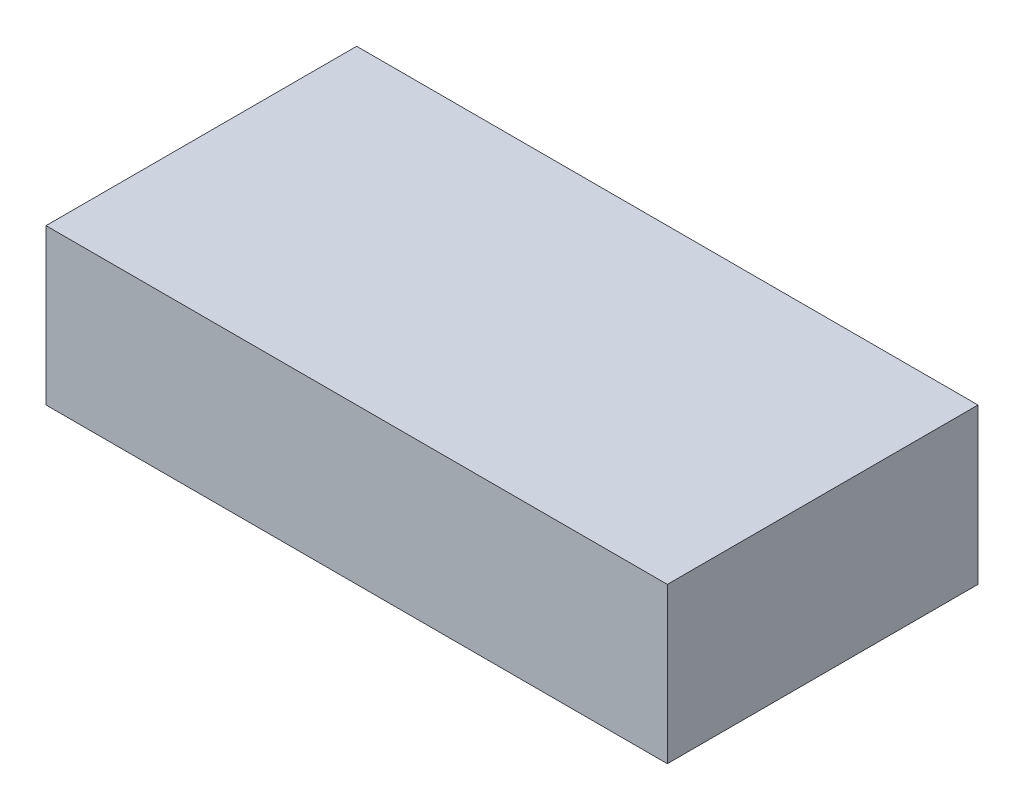
SolidWorks part; units mm, degrees
material "1060 Alloy"
ref_plane "Front Plane" through (0, 0, 0) normal (0, 0, 1) x (1, 0, 0)
ref_plane "Top Plane" through (0, 0, 0) normal (0, 1, 0) x (1, 0, 0)
ref_plane "Right Plane" through (0, 0, 0) normal (1, 0, 0) x (0, 0, -1)
sketch "Sketch1" plane through (0, 0, 0) normal (0, 1, 0) x (1, 0, 0)
  line L1 (-100, -50) -> (100, -50)
  line L2 (-100, -50) -> (-100, 50)
  line L3 (-100, 50) -> (100, 50)
  line L4 (100, -50) -> (100, 50)
  line L5 (-100, -50) -> (100, 50) construction
  line L6 (-100, 50) -> (100, -50) construction
  point P0 (0, 0)
  dimension "D1" = 200
  dimension "D2" = 100
extrude "Boss-Extrude1" add sketch "Sketch1" along normal blind 50
